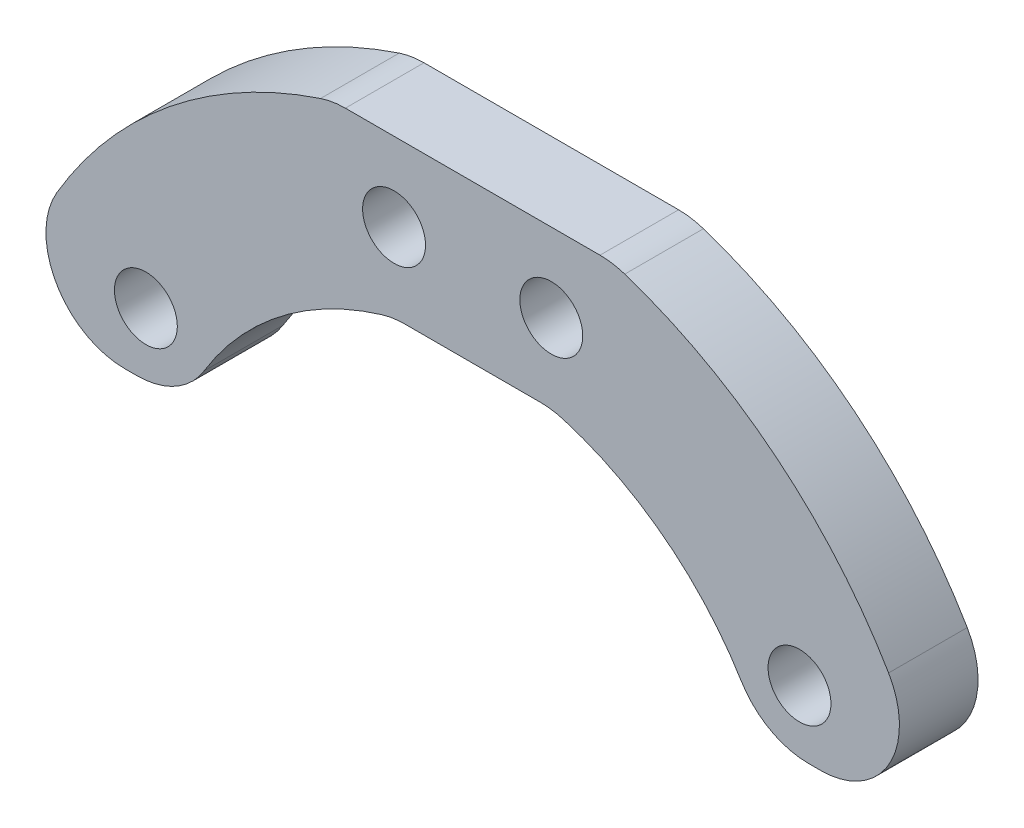
SolidWorks part; units mm, degrees
ref_plane "Front Plane" through (0, 0, 0) normal (0, 0, 1) x (1, 0, 0)
ref_plane "Top Plane" through (0, 0, 0) normal (0, 1, 0) x (1, 0, 0)
ref_plane "Right Plane" through (0, 0, 0) normal (1, 0, 0) x (0, 0, -1)
sketch "Sketch1" plane through (0, 0, 0) normal (0, 0, 1) x (1, 0, 0)
  line L0 (0, 19.3649) -> (0, 29.3649) construction
  line L1 (-29.6134, 8) -> (-18.3303, 8)
  line L2 (18.3303, 8) -> (29.6134, 8)
  line L4 (8.8689, 29.3649) -> (-8.8689, 29.3649)
  line L5 (-5, 24.3649) -> (5, 24.3649) construction
  line L6 (-5, 19.3649) -> (5, 19.3649)
  circle A3 centre (0, 24) radius 2 construction
  arc A7 (18.3303, 8) -> (5, 19.3649) centre (0, 0) ccw
  circle A14 centre (0, 0) radius 24 construction
  circle A15 centre (20.7846, 12) radius 2
  circle A19 centre (-20.7846, 12) radius 2
  arc A20 (29.6134, 8) -> (8.8689, 29.3649) centre (0, 0) ccw
  circle A21 centre (-20.7846, -12) radius 2 [skipped]
  circle A22 centre (0, -24) radius 2 [skipped]
  circle A23 centre (20.7846, -12) radius 2 [skipped]
  arc A24 (-8.8689, 29.3649) -> (-29.6134, 8) centre (0, 0) ccw
  arc A25 (-5, 19.3649) -> (-18.3303, 8) centre (0, 0) ccw
  circle A27 centre (-5, 24.3649) radius 2
  circle A28 centre (5, 24.3649) radius 2
  point P11 (5.2018, 24.3649)
  point P16 (0, 0)
  dimension "D1" = 48
  dimension "D2" = 20
  dimension "D3" = 4
  dimension "D5" = 61.35
  dimension "D10" = 4
  dimension "D12" = 4
  dimension "D4" = 6
  dimension "D6" = 8
  dimension "D7" = 10
  dimension "D8" = 10
  dimension "D9" = 5
  dimension "D11" = 5
  dimension "D13" = 5
extrude "Boss-Extrude1" add sketch "Sketch1" along normal blind 5
fillet "Fillet1" radius 5 8 edges at (-5, 19.3649, 2.5) (5, 19.3649, 2.5) (29.6134, 8, 2.5) (18.3303, 8, 2.5) (-29.6134, 8, 2.5) (-18.3303, 8, 2.5) (-8.8689, 29.3649, 2.5) (8.8689, 29.3649, 2.5)
